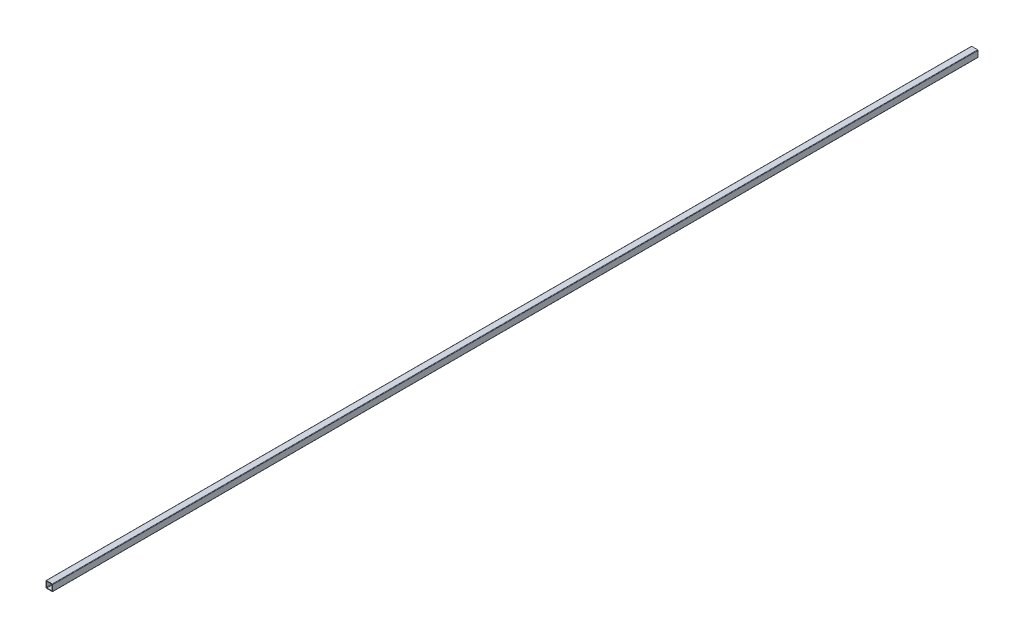
SolidWorks part; units mm, degrees
material "ASTM A500 Grade B Steel"
ref_plane "Front Plane" through (0, 0, 0) normal (0, 0, 1) x (1, 0, 0)
ref_plane "Top Plane" through (0, 0, 0) normal (0, 1, 0) x (1, 0, 0)
ref_plane "Right Plane" through (0, 0, 0) normal (1, 0, 0) x (0, 0, -1)
sketch "Sketch1" plane through (0, 0, 0) normal (0, 0, 1) x (1, 0, 0)
  line L0 (5.3086, -2.7686) -> (32.7914, -2.7686)
  line L1 (2.54, 0) -> (35.56, 0)
  line L2 (0, -2.54) -> (0, -35.56)
  line L3 (2.54, -38.1) -> (35.56, -38.1)
  line L4 (38.1, -2.54) -> (38.1, -35.56)
  line L5 (35.3314, -5.3086) -> (35.3314, -32.7914)
  line L6 (5.3086, -35.3314) -> (32.7914, -35.3314)
  line L7 (2.7686, -5.3086) -> (2.7686, -32.7914)
  line L8 (0, 0) -> (0, -38.1) construction
  line L9 (0, -38.1) -> (38.1, -38.1) construction
  line L10 (38.1, 0) -> (38.1, -38.1) construction
  line L11 (2.7686, -2.7686) -> (2.7686, -35.3314) construction
  line L12 (2.7686, -35.3314) -> (35.3314, -35.3314) construction
  line L13 (35.3314, -2.7686) -> (35.3314, -35.3314) construction
  line L14 (2.7686, -2.7686) -> (35.3314, -2.7686) construction
  line L15 (0, 0) -> (38.1, 0) construction
  arc A0 (0, -35.56) -> (2.54, -38.1) centre (2.54, -35.56) ccw
  arc A1 (38.1, -35.56) -> (35.56, -38.1) centre (35.56, -35.56) cw
  arc A2 (2.7686, -32.7914) -> (5.3086, -35.3314) centre (5.3086, -32.7914) ccw
  arc A3 (32.7914, -35.3314) -> (35.3314, -32.7914) centre (32.7914, -32.7914) ccw
  arc A4 (35.3314, -5.3086) -> (32.7914, -2.7686) centre (32.7914, -5.3086) ccw
  arc A5 (38.1, -2.54) -> (35.56, 0) centre (35.56, -2.54) ccw
  arc A6 (0, -2.54) -> (2.54, 0) centre (2.54, -2.54) cw
  arc A7 (5.3086, -2.7686) -> (2.7686, -5.3086) centre (5.3086, -5.3086) ccw
  point P12 (0, -38.1)
  dimension "D4" = 2.54
  dimension "D3" = 2.7686
extrude "Boss-Extrude1" add sketch "Sketch1" along normal blind 5243.8
